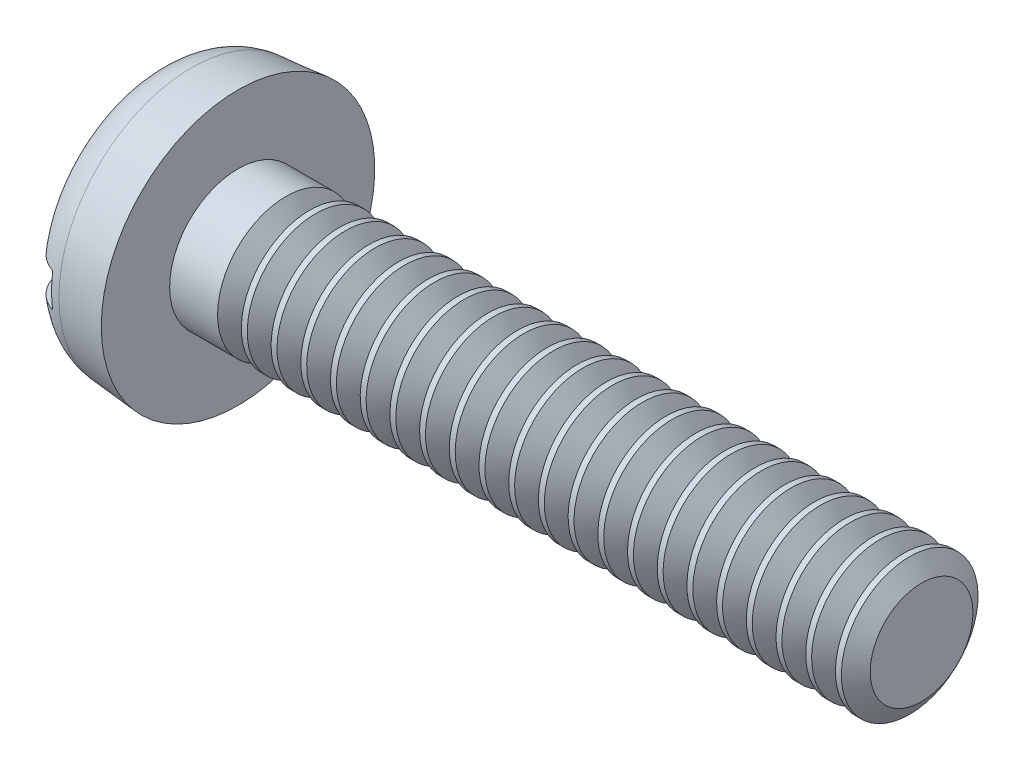
SolidWorks part; units mm, degrees
ref_plane "Plane1" through (0, 0, 0) normal (0, 0, 1) x (1, 0, 0)
ref_plane "Plane2" through (0, 0, 0) normal (0, 1, 0) x (1, 0, 0)
ref_plane "Plane3" through (0, 0, 0) normal (1, 0, 0) x (0, 0, -1)
sketch "BodySke" plane through (0, 0, 0) normal (0, 0, 1) x (1, 0, 0)
  line L0 (1, 0.8) -> (1, 1.6)
  line L1 (0, 0) -> (0, 1.5125)
  line L2 (-25.4, 0) -> (127, 0) construction
  line L3 (9, 0) -> (0, 0)
  line L4 (1, 0.8) -> (9, 0.8)
  line L5 (9, 0.8) -> (9, 0)
  line L6 (0, 1.5125) -> (1, 1.6)
  line L9 (1.35, 2.3875) -> (1.35, -7.1375) construction
  line L10 (1, 6.35) -> (1, -3.175) construction
  dimension "Head_ht" = 1
  dimension "Diameter" = 1.6
  dimension "Length" = 8
  dimension "Head_dia" = 3.2
  dimension "Advance" = 0.35
  dimension "Thread_nom" = 8
  dimension "Head_side_angle" = 5
revolve "Base-Revolve" add sketch "BodySke"
cosmetic thread "ThreadCosmetic" [suppressed]
fillet "Fillet1" [suppressed] radius 0.1
fillet "Fillet2" radius 0.5 1 edges at (0, 0, 1.5125)
sketch "Sketch2" plane through (0, 0, 0) normal (1, 0, 0) x (0, 0, -1)
  line L0 (1.6, -0.2) -> (-1.6, -0.2)
  line L1 (1.6, -0.2) -> (1.6, 0.2)
  line L2 (-1.6, 0.2) -> (1.6, 0.2)
  line L3 (-1.6, 0.2) -> (-1.6, -0.2)
  dimension "D1" = 3.2
  dimension "D2" = 1.6
  dimension "Slot_width" = 0.4
  dimension "D3" = 0.2
extrude "Slot" cut sketch "Sketch2" along normal blind 0.35
sketch "ThdSchSke" plane through (0, 0, 0) normal (0, 0, 1) x (1, 0, 0)
  line L0 (1.7, -0.601) -> (1.5607, -0.8)
  line L1 (1.7, -0.601) -> (1.8393, -0.8)
  line L2 (1.8393, -0.8) -> (1.8393, -1)
  line L3 (-3.175, 0) -> (5.1513, 0) construction
  line L5 (1.8393, -1) -> (1.5607, -1)
  line L6 (1.5607, -1) -> (1.5607, -0.8)
  dimension "Thread_minor" = 1.202
  dimension "Diameter" = 1.6
  dimension "Start" = 1.7
  dimension "SideAngle" = 55
  dimension "VeeAngle" = 70
  dimension "Overcut" = 2
revolve "ThreadSchematic" cut sketch "ThdSchSke" angle 360 about L3
pattern_linear "ThdSchPat" count 22 spacing 0.3476 along (1, 0, 0) of "ThreadSchematic"
equation "\"D1@Sketch2\" = \"Head_dia@BodySke\""
equation "\"D2@Sketch2\" = \"D1@Sketch2\" / 2"
equation "\"D3@Sketch2\" = \"Slot_width@Sketch2\" / 2"
equation "\"Thread_length@ThreadCosmetic\" = ((sgn( (\"Length@BodySke\" - \"Advance@BodySke\" * 2.0 ) - \"Thread_nom@BodySke\" )-1)*( (\"Length@BodySke\" - \"Advance@BodySke\"  * 2.0) - \"Thread_nom@BodySke\" ))/-2+ \"Thread_nom@BodySke\""
equation "\"Thread_minor@ThdSchSke\" = \"Thread_minor@ThreadCosmetic\""
equation "\"Diameter@ThdSchSke\" = \"Diameter@BodySke\""
equation "\"Overcut@ThdSchSke\" = \"Diameter@BodySke\" * 1.25"
equation "\"Start@ThdSchSke\" = \"Head_ht@BodySke\" + \"Length@BodySke\" - \"Thread_length@ThreadCosmetic\"  '---Non-countersunk---"
equation "\"Num_threads@ThdSchPat\" = int( \"Thread_length@ThreadCosmetic\" / \"Advance@BodySke\" + 0.999 )  + 1"
equation "\"Advance@ThdSchPat\" = \"Thread_length@ThreadCosmetic\" /  (\"Num_threads@ThdSchPat\" - 1) 'relax it"
